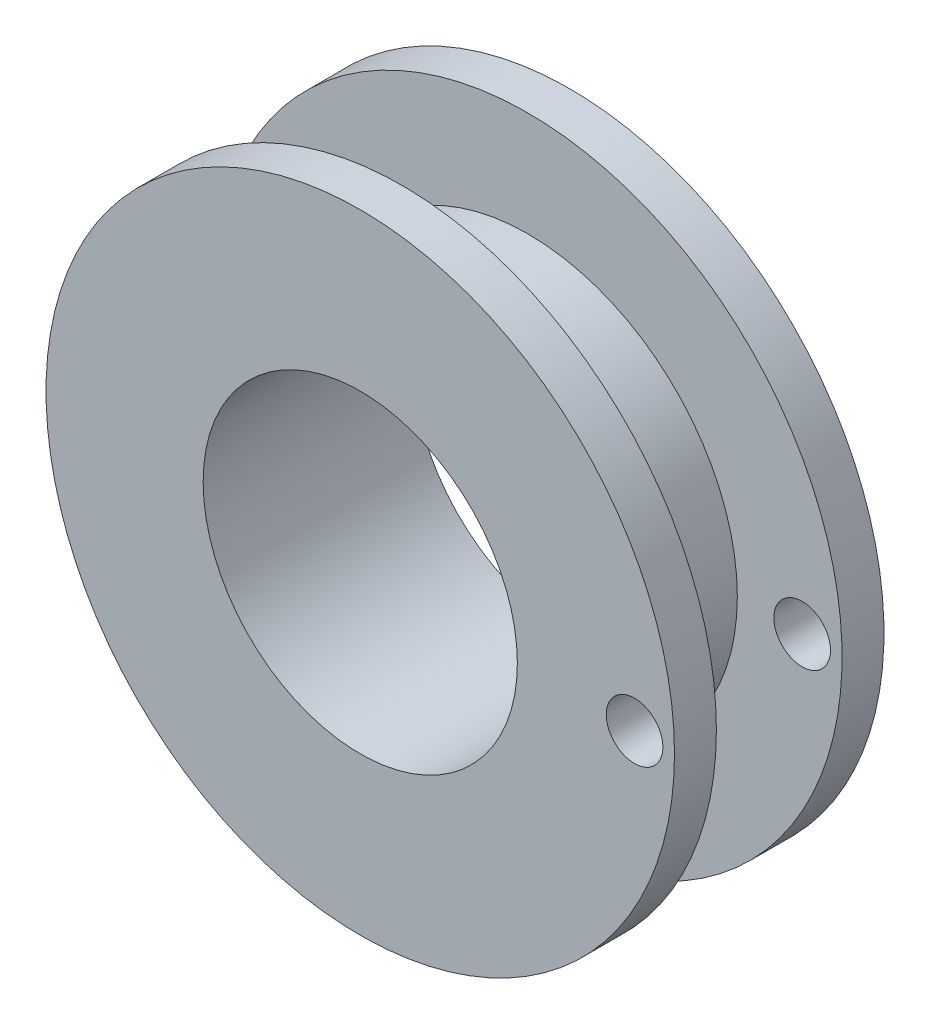
SolidWorks part; units mm, degrees
material "황동"
ref_plane "정면" through (0, 0, 0) normal (0, 0, 1) x (1, 0, 0)
ref_plane "윗면" through (0, 0, 0) normal (0, 1, 0) x (1, 0, 0)
ref_plane "우측면" through (0, 0, 0) normal (1, 0, 0) x (0, 0, -1)
sketch "스케치2" plane through (0, 0, 0) normal (0, 0, 1) x (1, 0, 0)
  circle A0 centre (0, 0) radius 10
  dimension "D1" = 20
extrude "보스-돌출1" add sketch "스케치2" along normal blind 6
sketch "스케치3" plane through (0, 0, 0) normal (0, 0, -1) x (-1, 0, 0)
  circle A0 centre (0, 0) radius 15
  dimension "D1" = 30
extrude "보스-돌출2" add sketch "스케치3" along normal blind 2
sketch "스케치4" plane through (0, 0, 6) normal (0, 0, 1) x (1, 0, 0)
  circle A0 centre (0, 0) radius 15
  dimension "D1" = 30
extrude "보스-돌출3" add sketch "스케치4" along normal blind 2
sketch "스케치5" plane through (0, 0, 8) normal (0, 0, 1) x (1, 0, 0)
  circle A0 centre (0, 0) radius 7.5
  dimension "D1" = 15
extrude "컷-돌출1" cut sketch "스케치5" against normal through all both
sketch "스케치6" plane through (0, 0, 8) normal (0, 0, 1) x (1, 0, 0)
  circle A0 centre (13.0946, 0) radius 1.3518
extrude "컷-돌출2" cut sketch "스케치6" against normal through all both
